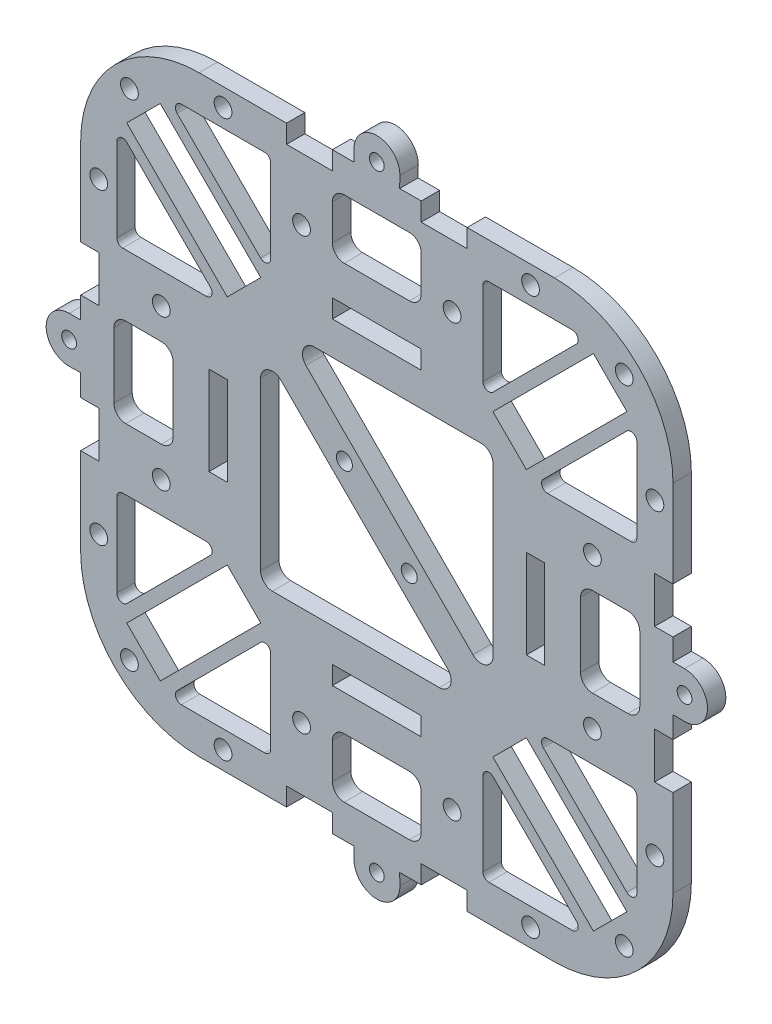
SolidWorks part; units mm, degrees
ref_plane "Front Plane" through (0, 0, 0) normal (0, 0, 1) x (1, 0, 0)
ref_plane "Top Plane" through (0, 0, 0) normal (0, 1, 0) x (1, 0, 0)
ref_plane "Right Plane" through (0, 0, 0) normal (1, 0, 0) x (0, 0, -1)
sketch "Sketch1" plane through (0, 0, 0) normal (0, 0, 1) x (1, 0, 0)
  line L0 (-29.1884, 29.8964) -> (59.0959, -58.3879) construction
  line L1 (11.1013, -64.2458) -> (7.4538, -64.2458)
  line L2 (-31.9462, -6.7458) -> (-31.9462, 1.0042)
  line L3 (-0.2962, -64.2458) -> (-15.0462, -64.2458)
  line L4 (7.4538, -61.1458) -> (-0.2962, -61.1458)
  line L5 (-26.814, -56.0135) -> (56.7216, 27.522) construction
  line L6 (-35.0462, 3.2542) -> (64.9538, 3.2542) construction
  line L7 (-35.0462, 3.2542) -> (-35.0462, -31.7458) construction
  line L8 (-35.0462, -31.7458) -> (64.9538, -31.7458) construction
  line L9 (-27.268, 22.3192) -> (-21.6112, 27.976)
  line L10 (-27.268, 22.3192) -> (-10.2975, 5.3486)
  line L11 (-10.2975, 5.3486) -> (-4.6406, 11.0055)
  line L12 (-21.6112, 27.976) -> (-4.6406, 11.0055)
  line L13 (64.9538, 3.2542) -> (64.9538, -31.7458) construction
  line L14 (51.5188, 27.976) -> (34.5482, 11.0055)
  line L15 (40.205, 5.3486) -> (34.5482, 11.0055)
  line L16 (57.1756, 22.3192) -> (40.205, 5.3486)
  line L17 (57.1756, 22.3192) -> (51.5188, 27.976)
  line L19 (57.1756, -50.8108) -> (51.5188, -56.4676)
  line L20 (57.1756, -50.8108) -> (40.205, -33.8402)
  line L21 (40.205, -33.8402) -> (34.5482, -39.497)
  line L22 (51.5188, -56.4676) -> (34.5482, -39.497)
  line L23 (-31.9462, -21.7458) -> (-31.9462, -29.4958)
  line L24 (-35.0462, -10.3933) -> (-35.0462, -6.7458)
  line L25 (66.9038, -18.1433) -> (64.9538, -18.0982)
  line L26 (66.9038, -10.3933) -> (64.9538, -10.3933)
  line L27 (64.9538, -21.7458) -> (64.9538, -18.0982)
  line L28 (-35.0462, -21.7458) -> (-31.9462, -21.7458)
  line L29 (64.9538, -6.7458) -> (61.8538, -6.7458)
  line L30 (64.9538, -21.7458) -> (61.8538, -21.7458)
  line L31 (64.9538, -10.3933) -> (64.9538, -6.7458)
  line L32 (22.4538, -64.2458) -> (18.8062, -64.2458)
  line L33 (30.2038, -61.1458) -> (30.2038, -64.2458)
  line L34 (11.1013, -66.1958) -> (11.1013, -64.2458)
  line L35 (-0.2962, -61.1458) -> (-0.2962, -64.2458)
  line L36 (18.8513, -66.1958) -> (18.8062, -64.2458)
  line L37 (-35.0462, -6.7458) -> (-31.9462, -6.7458)
  line L38 (22.4538, -64.2458) -> (22.4538, -61.1458)
  line L39 (22.4538, -61.1458) -> (30.2038, -61.1458)
  line L40 (7.4538, -64.2458) -> (7.4538, -61.1458)
  line L41 (30.2038, -64.2458) -> (44.9538, -64.2458)
  line L42 (-21.6112, -56.4676) -> (-4.6406, -39.497)
  line L43 (-10.2975, -33.8402) -> (-4.6406, -39.497)
  line L44 (-27.268, -50.8108) -> (-10.2975, -33.8402)
  line L45 (-27.268, -50.8108) -> (-21.6112, -56.4676)
  line L50 (-35.0462, -21.7458) -> (-35.0462, -18.0982)
  line L59 (-36.9962, -10.3933) -> (-35.0462, -10.3933)
  line L60 (-36.9962, -18.1433) -> (-35.0462, -18.0982)
  line L61 (-31.9462, -29.4958) -> (-35.0462, -29.4958)
  line L62 (30.2038, 35.7542) -> (44.9538, 35.7542)
  line L63 (7.4538, 35.7542) -> (7.4538, 32.6542)
  line L64 (22.4538, 32.6542) -> (30.2038, 32.6542)
  line L65 (22.4538, 35.7542) -> (22.4538, 32.6542)
  line L66 (18.8513, 37.7042) -> (18.8062, 35.7542)
  line L67 (-35.0462, -29.4958) -> (-35.0462, -44.2458)
  line L68 (-0.2962, 32.6542) -> (-0.2962, 35.7542)
  line L69 (11.1013, 37.7042) -> (11.1013, 35.7542)
  line L70 (-31.9462, 1.0042) -> (-35.0462, 1.0042)
  line L71 (-35.0462, 1.0042) -> (-35.0462, 15.7542)
  line L72 (64.9538, -29.4958) -> (64.9538, -44.2458)
  line L73 (61.8538, -29.4958) -> (64.9538, -29.4958)
  line L74 (61.8538, -21.7458) -> (61.8538, -29.4958)
  line L75 (61.8538, -6.7458) -> (61.8538, 1.0042)
  line L76 (61.8538, 1.0042) -> (64.9538, 1.0042)
  line L77 (64.9538, 1.0042) -> (64.9538, 15.7542)
  line L78 (30.2038, 32.6542) -> (30.2038, 35.7542)
  line L79 (22.4538, 35.7542) -> (18.8062, 35.7542)
  line L80 (7.4538, 32.6542) -> (-0.2962, 32.6542)
  line L81 (-0.2962, 35.7542) -> (-15.0462, 35.7542)
  line L82 (11.1013, 35.7542) -> (7.4538, 35.7542)
  line L90 (7.4538, -39.497) -> (22.4538, -39.497)
  line L91 (7.4538, -39.497) -> (7.4538, -42.597)
  line L92 (7.4538, -42.597) -> (22.4538, -42.597)
  line L93 (22.4538, -39.497) -> (22.4538, -42.597)
  line L94 (40.205, -21.7458) -> (43.305, -21.7458)
  line L95 (43.305, -21.7458) -> (43.305, -6.7458)
  line L96 (40.205, -6.7458) -> (43.305, -6.7458)
  line L97 (40.205, -21.7458) -> (40.205, -6.7458)
  line L99 (-10.2975, -21.7458) -> (-10.2975, -6.7458)
  line L100 (-10.2975, -6.7458) -> (-13.3975, -6.7458)
  line L101 (-13.3975, -21.7458) -> (-13.3975, -6.7458)
  line L102 (-10.2975, -21.7458) -> (-13.3975, -21.7458)
  line L103 (22.4538, 11.0055) -> (22.4538, 14.1055)
  line L104 (7.4538, 14.1055) -> (22.4538, 14.1055)
  line L105 (7.4538, 11.0055) -> (7.4538, 14.1055)
  line L106 (7.4538, 11.0055) -> (22.4538, 11.0055)
  line L112 (14.9538, -0.1958) -> (14.9538, -28.2958) construction
  line L115 (-10.0962, -14.2458) -> (40.0038, -14.2458) construction
  line L123 (20.4263, -19.7183) -> (21.2041, -20.4961) construction
  line L150 (20.4263, -23.6225) -> (34.2149, -9.8339) construction
  line L151 (20.4263, -23.6225) -> (5.5771, -8.7733) construction
  line L152 (5.5771, -8.7733) -> (19.3656, 5.0153) construction
  line L153 (34.2149, -9.8339) -> (19.3656, 5.0153) construction
  line L154 (20.4263, -19.7183) -> (19.6485, -20.4961) construction
  line L155 (-1.2533, -2.2813) -> (26.9183, -30.4529)
  line L156 (9.4813, -8.7733) -> (20.4263, -19.7183) construction
  line L157 (2.9893, 1.9613) -> (31.1609, -26.2102)
  line L158 (4.4035, 5.3755) -> (32.5751, 5.3755)
  line L159 (9.4813, -8.7733) -> (11.6026, -6.6519) construction
  line L160 (14.9538, -14.2458) -> (17.0751, -12.1245) construction
  line L161 (34.5751, 3.3755) -> (34.5751, -24.796)
  line L162 (-2.6675, -33.8671) -> (25.504, -33.8671)
  line L163 (-4.6675, -3.6955) -> (-4.6675, -31.8671)
  line L164 (21.868, 29.5618) -> (8.0396, 20.7334) construction
  line L165 (9.4538, 30.1476) -> (20.4538, 30.1476)
  line L166 (7.4538, 28.1476) -> (7.4538, 22.1476)
  line L167 (43.0335, 19.4908) -> (41.6193, 20.905) construction
  line L168 (33.8693, 29.655) -> (47.955, 29.655)
  line L169 (32.8693, 14.5692) -> (32.8693, 28.655)
  line L170 (34.5764, 13.8621) -> (48.6622, 27.9479)
  line L171 (54.3472, 25.1476) -> (37.3766, 8.1771) construction
  line L172 (43.0616, 5.3768) -> (57.1474, 19.4626)
  line L173 (43.7688, 3.6697) -> (57.8545, 3.6697)
  line L174 (58.8545, 4.6697) -> (58.8545, 18.7555)
  line L175 (43.7688, -32.1613) -> (57.8545, -32.1613)
  line L176 (58.8545, -33.1613) -> (58.8545, -47.247)
  line L177 (43.0616, -33.8684) -> (57.1474, -47.9542)
  line L178 (34.5764, -42.3536) -> (48.6622, -56.4394)
  line L179 (32.8693, -43.0608) -> (32.8693, -57.1465)
  line L180 (33.8693, -58.1465) -> (47.955, -58.1465)
  line L181 (-2.9617, 14.5692) -> (-2.9617, 28.655)
  line L182 (-3.9617, -58.1465) -> (-18.0475, -58.1465)
  line L183 (-2.9617, -43.0608) -> (-2.9617, -57.1465)
  line L184 (-4.6688, -42.3536) -> (-18.7546, -56.4394)
  line L185 (-13.8612, -32.1613) -> (-27.947, -32.1613)
  line L186 (-13.1541, -33.8684) -> (-27.2399, -47.9542)
  line L187 (-28.947, -33.1613) -> (-28.947, -47.247)
  line L188 (-28.947, 4.6697) -> (-28.947, 18.7555)
  line L189 (-13.8612, 3.6697) -> (-27.947, 3.6697)
  line L190 (-13.1541, 5.3768) -> (-27.2399, 19.4626)
  line L191 (-27.268, 22.3192) -> (-10.2975, 5.3486)
  line L192 (-4.6688, 13.8621) -> (-18.7546, 27.9479)
  line L193 (-3.9617, 29.655) -> (-18.0475, 29.655)
  line L194 (9.4538, 20.1476) -> (20.4538, 20.1476)
  line L195 (22.4538, 28.1476) -> (22.4538, 22.1476)
  line L196 (14.9538, 32.6542) -> (14.9538, 14.1055) construction
  line L197 (21.868, -58.0534) -> (8.0396, -49.225) construction
  line L198 (22.4538, -56.6392) -> (22.4538, -50.6392)
  line L199 (9.4538, -48.6392) -> (20.4538, -48.6392)
  line L200 (7.4538, -56.6392) -> (7.4538, -50.6392)
  line L201 (9.4538, -58.6392) -> (20.4538, -58.6392)
  line L202 (-29.4396, -19.7458) -> (-29.4396, -8.7458)
  line L203 (57.3472, -21.7458) -> (51.3472, -21.7458)
  line L204 (-19.4396, -19.7458) -> (-19.4396, -8.7458)
  line L205 (59.3472, -19.7458) -> (59.3472, -8.7458)
  line L206 (58.7614, -7.3316) -> (49.933, -21.16) construction
  line L207 (-27.4396, -6.7458) -> (-21.4396, -6.7458)
  line L208 (-28.8538, -7.3316) -> (-20.0254, -21.16) construction
  line L209 (49.3472, -19.7458) -> (49.3472, -8.7458)
  line L210 (-27.4396, -21.7458) -> (-21.4396, -21.7458)
  line L211 (57.3472, -6.7458) -> (51.3472, -6.7458)
  line L212 (-19.4396, -14.2458) -> (49.3472, -14.2458) construction
  arc A0 (-36.9962, -18.1433) -> (-36.9962, -10.3933) centre (-36.9962, -14.2683) cw
  circle A1 centre (-36.9962, -14.2458) radius 1.25
  circle A2 centre (66.9038, -14.2458) radius 1.25
  arc A3 (66.9038, -18.1433) -> (66.9038, -10.3933) centre (66.9038, -14.2683) ccw
  arc A4 (18.8513, -66.1958) -> (11.1013, -66.1958) centre (14.9763, -66.1958) cw
  circle A5 centre (14.9538, -66.1958) radius 1.25
  circle A6 centre (14.9538, 37.7042) radius 1.25
  arc A7 (18.8513, 37.7042) -> (11.1013, 37.7042) centre (14.9763, 37.7042) ccw
  circle A8 centre (-26.814, -56.0135) radius 1.5
  circle A9 centre (56.7216, -56.0135) radius 1.5
  circle A10 centre (-31.9966, -40.2042) radius 1.5
  circle A11 centre (-11.0046, -61.1962) radius 1.5
  circle A12 centre (61.9042, -40.2042) radius 1.5
  circle A13 centre (40.9122, -61.1962) radius 1.5
  circle A14 centre (61.9042, 11.7126) radius 1.5
  circle A15 centre (56.7216, 27.522) radius 1.5
  circle A16 centre (40.9122, 32.7046) radius 1.5
  circle A17 centre (-11.0046, 32.7046) radius 1.5
  circle A18 centre (-26.814, 27.522) radius 1.5
  circle A19 centre (-31.9966, 11.7126) radius 1.5
  circle A20 centre (27.6616, 22.149) radius 1.5
  circle A21 centre (2.2461, 22.149) radius 1.5
  circle A22 centre (27.6616, -50.6378) radius 1.5
  circle A23 centre (2.2461, -50.6378) radius 1.5
  arc A24 (64.9538, 15.7542) -> (44.9538, 35.7542) centre (44.9538, 15.7542) ccw
  arc A25 (-35.0462, 15.7542) -> (-15.0462, 35.7542) centre (-15.0462, 15.7542) cw
  arc A26 (-35.0462, -44.2458) -> (-15.0462, -64.2458) centre (-15.0462, -44.2458) ccw
  arc A27 (64.9538, -44.2458) -> (44.9538, -64.2458) centre (44.9538, -44.2458) cw
  circle A28 centre (51.3486, -26.9522) radius 1.5
  circle A29 centre (51.3486, -1.5367) radius 1.5
  circle A30 centre (-21.4381, -26.9522) radius 1.5
  circle A31 centre (-21.4381, -1.5367) radius 1.5
  circle A48 centre (20.4263, -19.7183) radius 1.6607 construction
  circle A49 centre (9.4813, -8.7733) radius 1.6607 construction
  circle A50 centre (9.4813, -8.7733) radius 1.35
  circle A51 centre (20.4263, -19.7183) radius 1.35
  arc A52 (2.9893, 1.9613) -> (4.4035, 5.3755) centre (4.4035, 3.3755) cw
  arc A53 (34.5751, 3.3755) -> (32.5751, 5.3755) centre (32.5751, 3.3755) ccw
  arc A54 (34.5751, -24.796) -> (31.1609, -26.2102) centre (32.5751, -24.796) cw
  arc A55 (25.504, -33.8671) -> (26.9183, -30.4529) centre (25.504, -31.8671) ccw
  arc A56 (-2.6675, -33.8671) -> (-4.6675, -31.8671) centre (-2.6675, -31.8671) cw
  arc A57 (-1.2533, -2.2813) -> (-4.6675, -3.6955) centre (-2.6675, -3.6955) ccw
  arc A58 (7.4538, 28.1476) -> (9.4538, 30.1476) centre (9.4538, 28.1476) cw
  arc A59 (7.4538, 22.1476) -> (9.4538, 20.1476) centre (9.4538, 22.1476) ccw
  arc A60 (20.4538, 20.1476) -> (22.4538, 22.1476) centre (20.4538, 22.1476) ccw
  arc A61 (33.8693, 29.655) -> (32.8693, 28.655) centre (33.8693, 28.655) ccw
  arc A62 (34.5764, 13.8621) -> (32.8693, 14.5692) centre (33.8693, 14.5692) cw
  arc A63 (47.955, 29.655) -> (48.6622, 27.9479) centre (47.955, 28.655) cw
  arc A64 (58.8545, 18.7555) -> (57.1474, 19.4626) centre (57.8545, 18.7555) ccw
  arc A65 (43.0616, 5.3768) -> (43.7688, 3.6697) centre (43.7688, 4.6697) ccw
  arc A66 (58.8545, 4.6697) -> (57.8545, 3.6697) centre (57.8545, 4.6697) cw
  arc A67 (43.0616, -33.8684) -> (43.7688, -32.1613) centre (43.7688, -33.1613) cw
  arc A68 (58.8545, -47.247) -> (57.1474, -47.9542) centre (57.8545, -47.247) cw
  arc A69 (34.5764, -42.3536) -> (32.8693, -43.0608) centre (33.8693, -43.0608) ccw
  arc A70 (33.8693, -58.1465) -> (32.8693, -57.1465) centre (33.8693, -57.1465) cw
  arc A71 (58.8545, -33.1613) -> (57.8545, -32.1613) centre (57.8545, -33.1613) ccw
  arc A72 (47.955, -58.1465) -> (48.6622, -56.4394) centre (47.955, -57.1465) ccw
  arc A73 (-18.0475, -58.1465) -> (-18.7546, -56.4394) centre (-18.0475, -57.1465) cw
  arc A74 (-4.6688, -42.3536) -> (-2.9617, -43.0608) centre (-3.9617, -43.0608) cw
  arc A75 (-3.9617, -58.1465) -> (-2.9617, -57.1465) centre (-3.9617, -57.1465) ccw
  arc A76 (-28.947, -33.1613) -> (-27.947, -32.1613) centre (-27.947, -33.1613) cw
  arc A77 (-13.1541, -33.8684) -> (-13.8612, -32.1613) centre (-13.8612, -33.1613) ccw
  arc A78 (-28.947, -47.247) -> (-27.2399, -47.9542) centre (-27.947, -47.247) ccw
  arc A79 (-28.947, 4.6697) -> (-27.947, 3.6697) centre (-27.947, 4.6697) ccw
  arc A80 (-13.1541, 5.3768) -> (-13.8612, 3.6697) centre (-13.8612, 4.6697) cw
  arc A81 (-28.947, 18.7555) -> (-27.2399, 19.4626) centre (-27.947, 18.7555) cw
  arc A82 (-18.0475, 29.655) -> (-18.7546, 27.9479) centre (-18.0475, 28.655) ccw
  arc A83 (-4.6688, 13.8621) -> (-2.9617, 14.5692) centre (-3.9617, 14.5692) ccw
  arc A84 (-3.9617, 29.655) -> (-2.9617, 28.655) centre (-3.9617, 28.655) cw
  arc A85 (22.4538, 28.1476) -> (20.4538, 30.1476) centre (20.4538, 28.1476) ccw
  arc A86 (22.4538, -56.6392) -> (20.4538, -58.6392) centre (20.4538, -56.6392) cw
  arc A87 (20.4538, -48.6392) -> (22.4538, -50.6392) centre (20.4538, -50.6392) cw
  arc A88 (7.4538, -50.6392) -> (9.4538, -48.6392) centre (9.4538, -50.6392) cw
  arc A89 (7.4538, -56.6392) -> (9.4538, -58.6392) centre (9.4538, -56.6392) ccw
  arc A90 (-27.4396, -21.7458) -> (-29.4396, -19.7458) centre (-27.4396, -19.7458) cw
  arc A91 (57.3472, -6.7458) -> (59.3472, -8.7458) centre (57.3472, -8.7458) cw
  arc A92 (-21.4396, -21.7458) -> (-19.4396, -19.7458) centre (-21.4396, -19.7458) ccw
  arc A93 (51.3472, -21.7458) -> (49.3472, -19.7458) centre (51.3472, -19.7458) cw
  arc A94 (49.3472, -8.7458) -> (51.3472, -6.7458) centre (51.3472, -8.7458) cw
  arc A95 (57.3472, -21.7458) -> (59.3472, -19.7458) centre (57.3472, -19.7458) ccw
  arc A96 (-19.4396, -8.7458) -> (-21.4396, -6.7458) centre (-21.4396, -8.7458) ccw
  arc A97 (-27.4396, -6.7458) -> (-29.4396, -8.7458) centre (-27.4396, -8.7458) ccw
  point P35 (64.9538, -14.2458)
  point P68 (-35.0462, -14.2458)
  point P76 (14.9538, -64.2458)
  point P232 (64.9538, 35.7542)
  point P403 (22.4538, -58.6392)
  point P404 (7.4538, -48.6392)
  point P405 (7.4538, -58.6392)
  point P434 (59.3472, -6.7458)
  point P435 (49.3472, -21.7458)
  point P436 (59.3472, -21.7458)
  dimension "D7" = 20
  dimension "D16" = 2
  dimension "D2" = 100
  dimension "D3" = 35
  dimension "D5" = 3.1
  dimension "D6" = 7.75
  dimension "D14" = 1.1
  dimension "D15" = 1.1
extrude "Extrude1" add sketch "Sketch1" along normal blind 3.1
